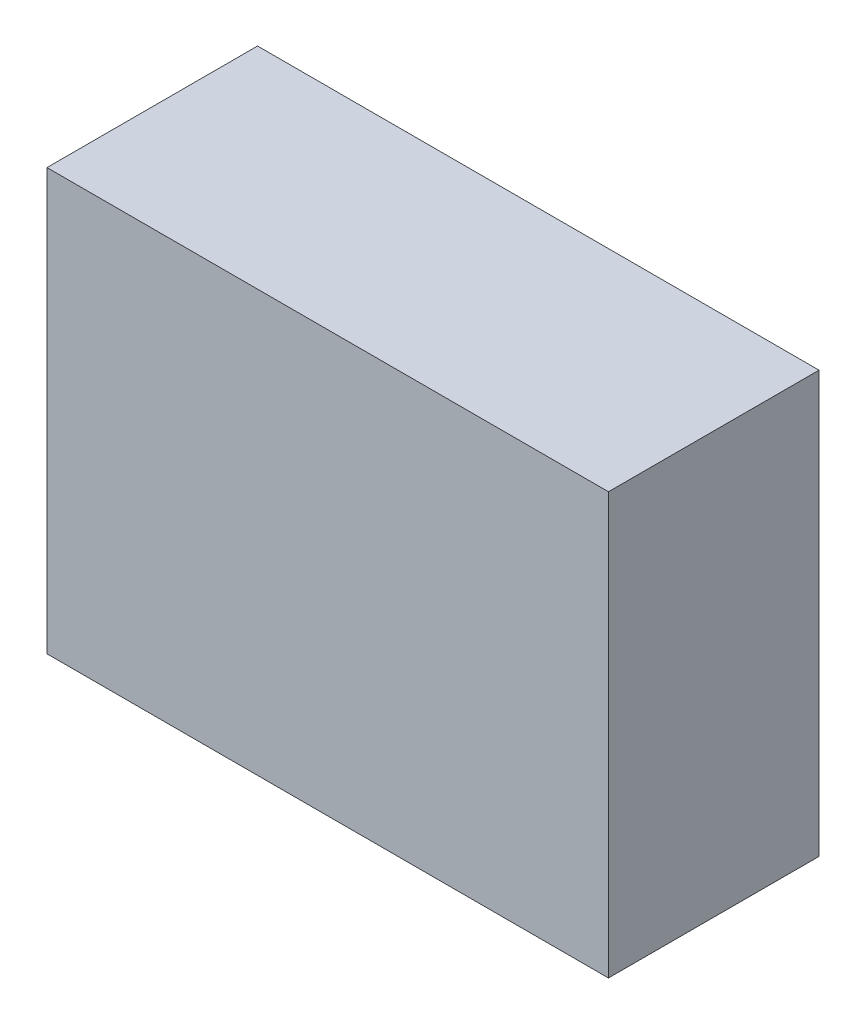
SolidWorks part; units mm, degrees
ref_plane "前视基准面" through (0, 0, 0) normal (0, 0, 1) x (1, 0, 0)
ref_plane "上视基准面" through (0, 0, 0) normal (0, 1, 0) x (1, 0, 0)
ref_plane "右视基准面" through (0, 0, 0) normal (1, 0, 0) x (0, 0, -1)
other "Configuration Table"
sketch "草图1" plane through (0, 0, 0) normal (0, 0, 1) x (1, 0, 0)
  line L1 (-4000, -3000) -> (4000, -3000)
  line L2 (-4000, -3000) -> (-4000, 3000)
  line L3 (-4000, 3000) -> (4000, 3000)
  line L4 (4000, -3000) -> (4000, 3000)
  line L5 (-4000, -3000) -> (4000, 3000) construction
  line L6 (-4000, 3000) -> (4000, -3000) construction
  point P0 (0, 0)
extrude "凸台-拉伸1" add sketch "草图1" along normal blind 3000
